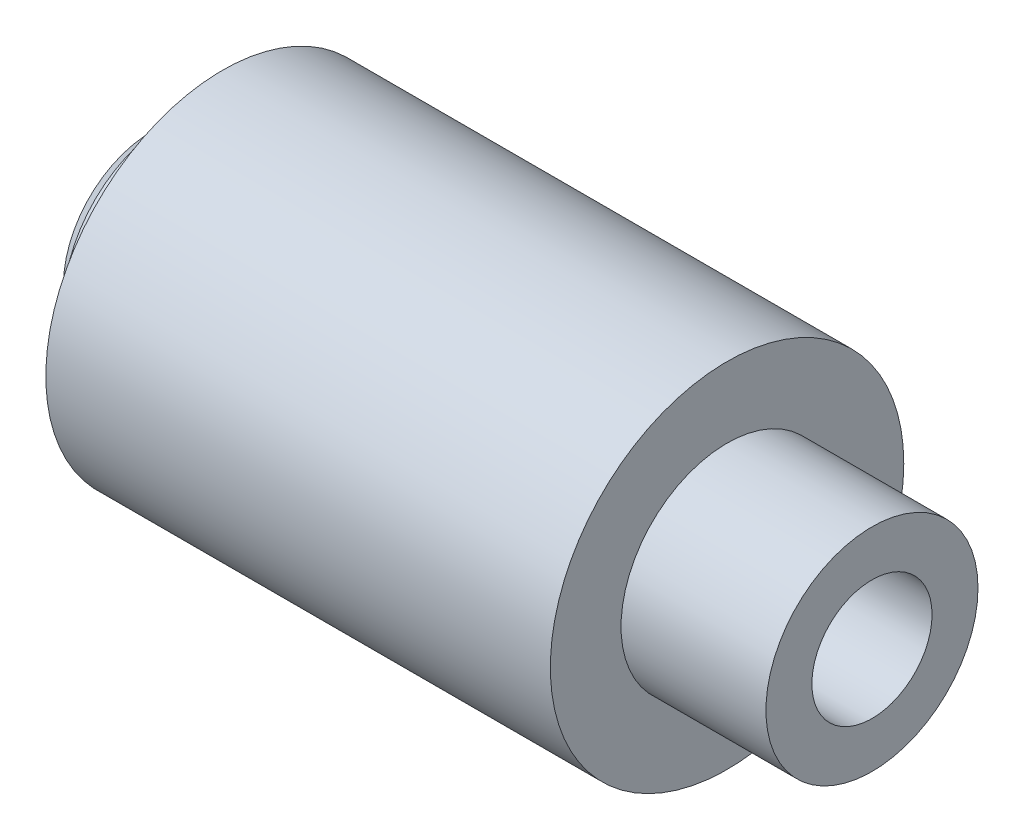
SolidWorks part; units mm, degrees
ref_plane "Plan de face" through (0, 0, 0) normal (0, 0, 1) x (1, 0, 0)
ref_plane "Plan de dessus" through (0, 0, 0) normal (0, 1, 0) x (1, 0, 0)
ref_plane "Plan de droite" through (0, 0, 0) normal (1, 0, 0) x (0, 0, -1)
sketch "Esquisse1" plane through (0, 0, 0) normal (1, 0, 0) x (0, 0, -1)
  circle A0 centre (0, 0) radius 5
  dimension "D1" = 10
extrude "Boss.-Extru.1" add sketch "Esquisse1" along normal blind 14.275
ref_plane "Plan1" through (3, 0, 0) normal (1, 0, 0) x (0, 0, -1)
sketch "Esquisse2" [suppressed] plane through (3, 0, 0) normal (1, 0, 0) x (0, 0, -1)
  line L0 (0, 4) -> (-4.4721, 4)
  line L1 (0, -4) -> (-4.4721, -4)
  circle A1 centre (0, 0) radius 6 construction
  circle A2 centre (0, 0) radius 4
  arc A3 (0, -4) -> (0, 4) centre (0, 0) ccw
  arc A4 (-4.4721, 4) -> (-4.4721, -4) centre (0, 0) ccw
  dimension "D1" = 2
sketch "Esquisse5" plane through (0, 0, 0) normal (-1, 0, 0) x (0, 0, 1)
  circle A0 centre (0, 0) radius 3
  dimension "D1" = 6
extrude "Boss.-Extru.2" add sketch "Esquisse5" along normal blind 2
chamfer "Chanfrein1" distance 0.5 angle 45 1 edges at (-2, 0, 3)
sketch "Esquisse6" plane through (14.275, 0, 0) normal (1, 0, 0) x (0, 0, -1)
  circle A0 centre (0, 0) radius 3
  dimension "D1" = 6
extrude "Boss.-Extru.3" add sketch "Esquisse6" along normal blind 4.1
hole_wizard "Dégagement M32" positions "Esquisse7" profile "Esquisse8" hole size "M3" standard "ISO" end condition up to next
sketch "Esquisse7" plane through (18.375, 0, 0) normal (1, 0, 0) x (0, 0, -1)
  point P0 (0, 0)
sketch "Esquisse8" plane through (18.375, 0, 0) normal (0, 1, 0) x (0, 0, -1)
  line L0 (0, 0) -> (0, 20.375)
  line L1 (0, 20.375) -> (1.7, 20.375)
  line L2 (1.7, 20.375) -> (1.7, 0)
  line L5 (1.7, 0) -> (0, 0)
  line L11 (0, -6.35) -> (0, 107.95) construction
  dimension "Diamètre du perçage jusqu'au prochain" = 3.4
  dimension "Profondeur du perçage jusqu'au prochain" = 20.375
